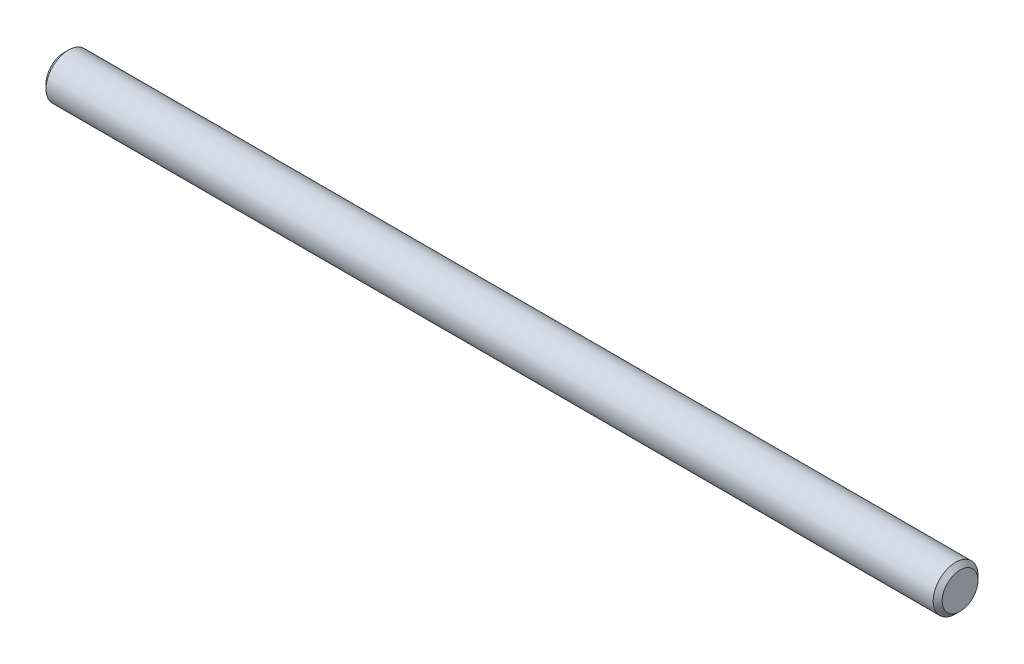
SolidWorks part; units mm, degrees
material "Stainless Steel 304"
ref_plane "Front Plane" through (0, 0, 0) normal (0, 0, 1) x (1, 0, 0)
ref_plane "Top Plane" through (0, 0, 0) normal (0, 1, 0) x (1, 0, 0)
ref_plane "Right Plane" through (0, 0, 0) normal (1, 0, 0) x (0, 0, -1)
sketch "Sketch1" plane through (0, 0, 0) normal (0, 0, 1) x (1, 0, 0)
  line L0 (-7.9375, 0) -> (7.9375, 0) construction
  line L1 (-7.9375, 0.3969) -> (-7.9375, -0.3969) construction
  line L2 (7.9375, 0.3969) -> (7.9375, -0.3969) construction
  dimension "Diameter" = 0.7937
  dimension "Length" = 15.875
sketch "Sketch2" plane through (0, 0, 0) normal (1, 0, 0) x (0, 0, -1)
  circle A0 centre (0, 0) radius 0.3969
extrude "Extrude1" add sketch "Sketch2" against normal up to vertex (7.9375 mm away) and the other way up to vertex (7.9375 mm away) up to point (-7.9375, 0, 0) other way up to point (7.9375, 0, 0)
chamfer "Chamfer1" distance 0.0794 angle 45 2 edges at (7.9375, 0, -0.3969) (-7.9375, 0, -0.3969)
equation "\"D1@Chamfer1\" = \"Diameter@Sketch1\"*.1"
